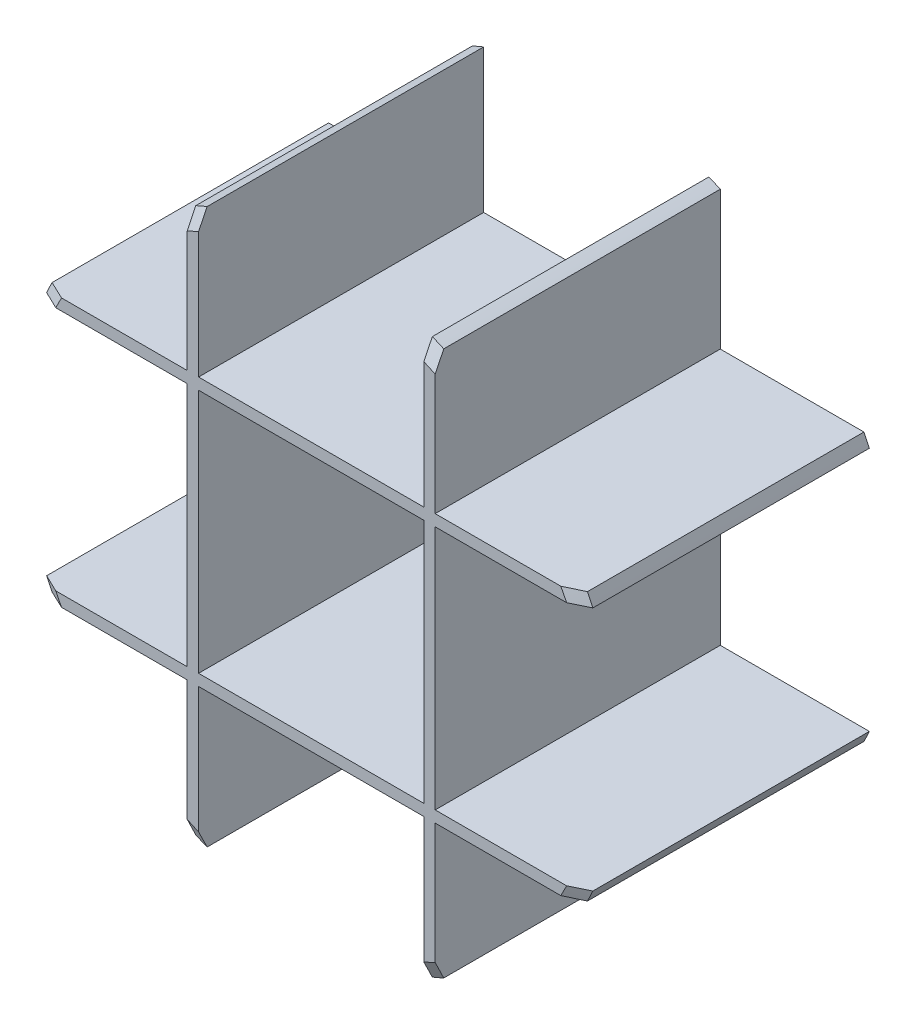
SolidWorks part; units mm, degrees
ref_plane "Front Plane" through (0, 0, 0) normal (0, 0, 1) x (1, 0, 0)
ref_plane "Top Plane" through (0, 0, 0) normal (0, 1, 0) x (1, 0, 0)
ref_plane "Right Plane" through (0, 0, 0) normal (1, 0, 0) x (0, 0, -1)
sketch "Sketch1" plane through (0, 0, 0) normal (0, 0, 1) x (1, 0, 0)
  line L0 (0, 55.2604) -> (0, -54.5137) construction
  line L1 (-75.506, 0) -> (67.9554, 0) construction
  line L2 (-19.75, 48.6435) -> (-19.75, 23.5)
  line L3 (19.75, 48.6435) -> (19.75, 23.5)
  line L4 (-47.8957, 21.5) -> (-21.75, 21.5)
  line L5 (-47.8957, -21.5) -> (-21.75, -21.5)
  line L6 (-21.75, 47.7827) -> (-21.75, 23.5)
  line L7 (-46.9468, -23.5) -> (-21.75, -23.5)
  line L8 (-46.9468, 23.5) -> (-21.75, 23.5)
  line L9 (21.75, 47.7827) -> (21.75, 23.5)
  line L10 (-21.75, 48.6435) -> (-21.75, -48.6435) construction
  line L11 (21.75, 48.6435) -> (21.75, -48.6435) construction
  line L12 (-47.8957, 23.5) -> (47.8957, 23.5) construction
  line L13 (-47.8957, -23.5) -> (47.8957, -23.5) construction
  line L14 (-19.75, 23.5) -> (19.75, 23.5)
  line L15 (-19.75, 21.5) -> (19.75, 21.5)
  line L16 (-47.8957, 21.5) -> (47.8957, 21.5) construction
  line L17 (-21.75, 21.5) -> (-21.75, -21.5)
  line L18 (-19.75, 21.5) -> (-19.75, -21.5)
  line L19 (-19.75, 48.6435) -> (-19.75, -48.6435) construction
  line L20 (21.75, 23.5) -> (46.9468, 23.5)
  line L21 (21.75, 21.5) -> (47.8957, 21.5)
  line L22 (19.75, 21.5) -> (19.75, -21.5)
  line L23 (19.75, 48.6435) -> (19.75, -48.6435) construction
  line L24 (21.75, 21.5) -> (21.75, -21.5)
  line L25 (21.75, -21.5) -> (47.8957, -21.5)
  line L26 (-47.8957, -21.5) -> (47.8957, -21.5) construction
  line L27 (21.75, -23.5) -> (46.9468, -23.5)
  line L28 (19.75, -23.5) -> (19.75, -48.6435)
  line L29 (21.75, -23.5) -> (21.75, -47.7827)
  line L30 (-19.75, -21.5) -> (19.75, -21.5)
  line L31 (-19.75, -23.5) -> (19.75, -23.5)
  line L32 (-21.75, -23.5) -> (-21.75, -47.7827)
  line L33 (-19.75, -23.5) -> (-19.75, -48.6435)
  arc A0 (-46.9468, 23.5) -> (-47.8957, 21.5) centre (0, 0) ccw construction
  arc A1 (-46.9468, 23.5) -> (-47.8957, 21.5) centre (0, 0) ccw
  arc A2 (21.75, 47.7827) -> (19.75, 48.6435) centre (0, 0) ccw construction
  arc A3 (21.75, 47.7827) -> (19.75, 48.6435) centre (0, 0) ccw
  arc A4 (-19.75, 48.6435) -> (-21.75, 47.7827) centre (0, 0) ccw construction
  arc A5 (-19.75, 48.6435) -> (-21.75, 47.7827) centre (0, 0) ccw
  arc A6 (47.8957, 21.5) -> (46.9468, 23.5) centre (0, 0) ccw construction
  arc A7 (47.8957, 21.5) -> (46.9468, 23.5) centre (0, 0) ccw
  arc A8 (46.9468, -23.5) -> (47.8957, -21.5) centre (0, 0) ccw construction
  arc A9 (46.9468, -23.5) -> (47.8957, -21.5) centre (0, 0) ccw
  arc A10 (19.75, -48.6435) -> (21.75, -47.7827) centre (0, 0) ccw construction
  arc A11 (19.75, -48.6435) -> (21.75, -47.7827) centre (0, 0) ccw
  arc A12 (-21.75, -47.7827) -> (-19.75, -48.6435) centre (0, 0) ccw construction
  arc A13 (-21.75, -47.7827) -> (-19.75, -48.6435) centre (0, 0) ccw
  arc A14 (-47.8957, -21.5) -> (-46.9468, -23.5) centre (0, 0) ccw construction
  arc A15 (-47.8957, -21.5) -> (-46.9468, -23.5) centre (0, 0) ccw
  dimension "D1" = 105
  dimension "D2" = 39.5
  dimension "D3" = 43
  dimension "D4" = 2
  dimension "D5" = 2
extrude "Boss-Extrude1" add sketch "Sketch1" along normal blind 50
sketch "Sketch2" plane through (0, 0, 0) normal (0, 1, 0) x (1, 0, 0)
  line L0 (0, 17.2126) -> (0, -69.8264) construction
  line L3 (-52.5, -48.5) -> (-23.44, -64)
  line L4 (-23.44, -64) -> (0, -64)
  line L5 (-52.5, -48.5) -> (-62.7308, -48.5)
  line L6 (-62.7308, -48.5) -> (-62.7308, -76.9249)
  line L7 (-62.7308, -76.9249) -> (0, -76.9249)
  line L8 (0, -76.9249) -> (0, -64)
  line L9 (-21.75, 0) -> (-46.9468, 0) construction
  dimension "D1" = 23.44
  dimension "D2" = 15.5
  dimension "D3" = 48.5
  dimension "D4" = 52.5
revolve "Cut-Revolve1" cut sketch "Sketch2" angle 360 about L0
